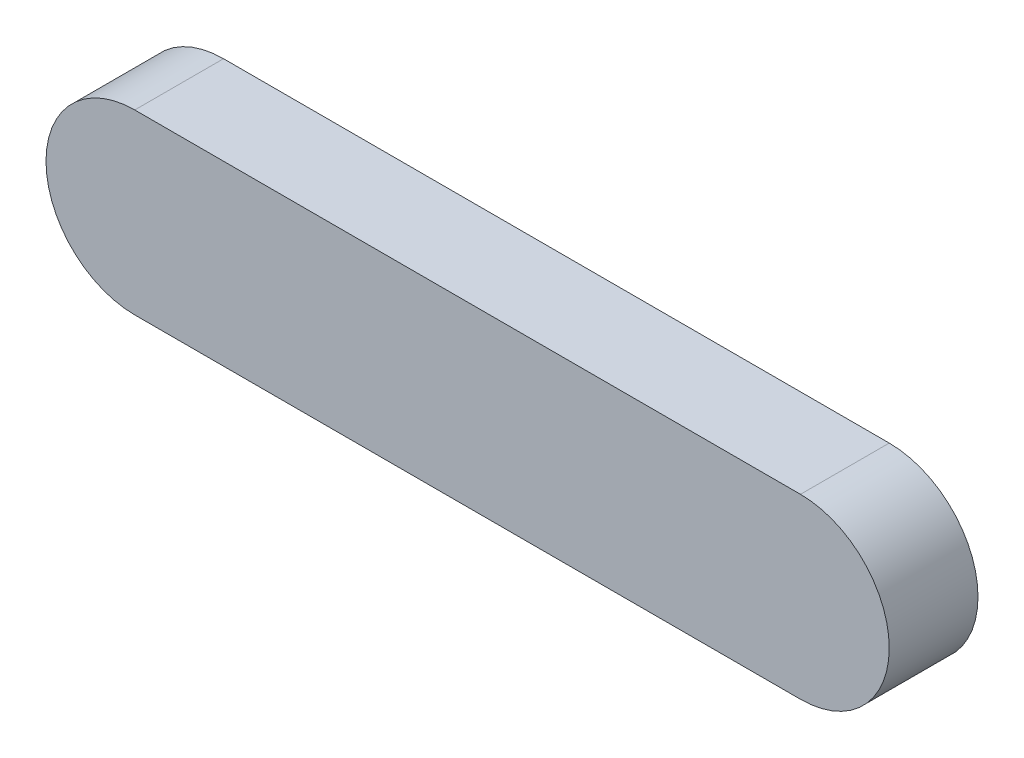
SolidWorks part; units mm, degrees
ref_plane "前视基准面" through (0, 0, 0) normal (0, 0, 1) x (1, 0, 0)
ref_plane "上视基准面" through (0, 0, 0) normal (0, 1, 0) x (1, 0, 0)
ref_plane "右视基准面" through (0, 0, 0) normal (1, 0, 0) x (0, 0, -1)
sketch "草图1" plane through (0, 0, 0) normal (0, 0, 1) x (1, 0, 0)
  line L3 (-75, 20) -> (75, 20)
  line L4 (75, -20) -> (-75, -20)
  arc A2 (75, 20) -> (75, -20) centre (75, 0) cw
  arc A3 (-75, 20) -> (-75, -20) centre (-75, 0) ccw
  point P8 (0, -20)
extrude "凸台-拉伸1" add sketch "草图1" along normal blind 20
